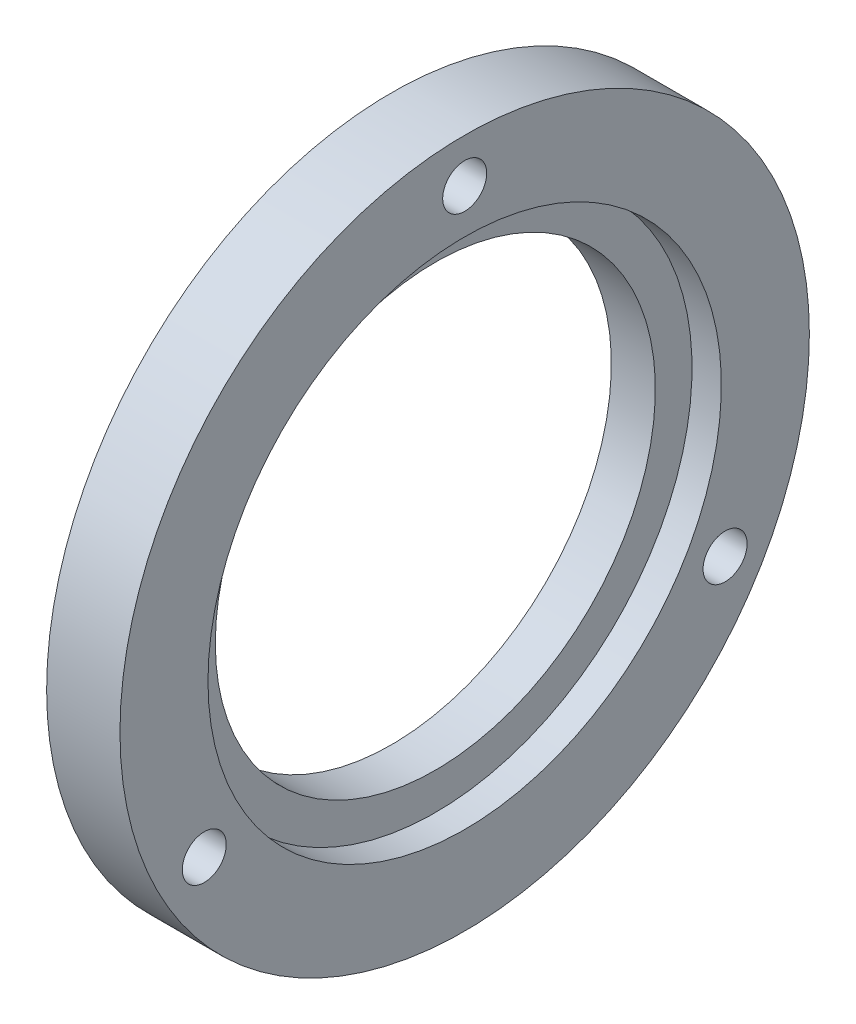
SolidWorks part; units mm, degrees
ref_plane "Front Plane" through (0, 0, 0) normal (0, 0, 1) x (1, 0, 0)
ref_plane "Top Plane" through (0, 0, 0) normal (0, 1, 0) x (1, 0, 0)
ref_plane "Right Plane" through (0, 0, 0) normal (1, 0, 0) x (0, 0, -1)
sketch "Sketch1" plane through (0, 0, 0) normal (0, 0, 1) x (1, 0, 0)
  line L0 (0, 0) -> (8.2353, 0) construction
  line L1 (0, 15) -> (0, 23.5)
  line L2 (0, 23.5) -> (5, 23.5)
  line L3 (5, 23.5) -> (5, 17.5)
  line L4 (5, 17.5) -> (3, 17.5)
  line L5 (3, 17.5) -> (3, 15)
  line L6 (3, 15) -> (0, 15)
  dimension "D1" = 5
  dimension "D2" = 3
  dimension "D3" = 23.5
  dimension "D4" = 17.5
  dimension "D5" = 15
revolve "Revolve1" add sketch "Sketch1" angle 360 about L0
sketch "Sketch2" plane through (0, 0, 0) normal (-1, 0, 0) x (0, 0, 1)
  line L0 (0, 0) -> (0, 20.5) construction
  circle A0 centre (0, 20.5) radius 1.5
  circle A1 centre (17.7535, -10.25) radius 1.5
  circle A2 centre (-17.7535, -10.25) radius 1.5
  point P10 (0, 0)
  dimension "D2" = 3
  dimension "D3" = 20.5
  dimension "D1" = 3
extrude "Cut-Extrude1" cut sketch "Sketch2" against normal through all both and the other way through all
